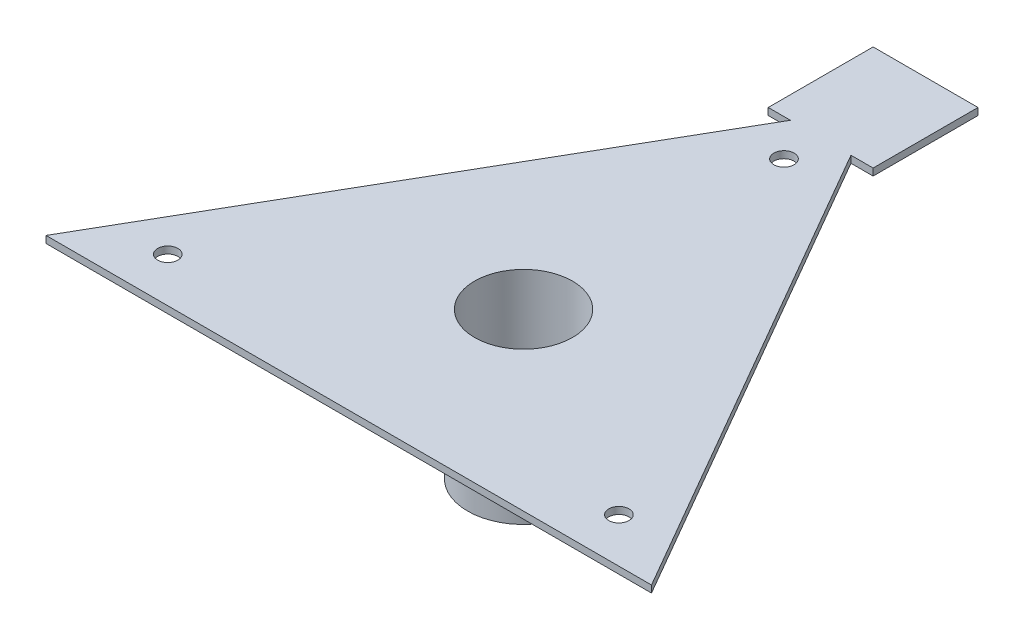
SolidWorks part; units mm, degrees
ref_plane "Front Plane" through (0, 0, 0) normal (0, 0, 1) x (1, 0, 0)
ref_plane "Top Plane" through (0, 0, 0) normal (0, 1, 0) x (1, 0, 0)
ref_plane "Right Plane" through (0, 0, 0) normal (1, 0, 0) x (0, 0, -1)
sketch "Sketch1" plane through (0, 0, 0) normal (0, 1, 0) x (1, 0, 0)
  line L0 (0, 0) -> (0, 50)
  line L1 (0, 0) -> (-43.3013, -25)
  line L2 (0, 0) -> (43.3013, -25)
  line L3 (0, 50) -> (-43.3013, -25)
  line L4 (0, 50) -> (43.3013, -25)
  line L5 (-43.3013, -25) -> (43.3013, -25)
extrude "Boss-Extrude3" add sketch "Sketch1" along normal blind 1.25 contours L4 L0 L2 | L0 L3 L1 | L1 L5 L2
sketch "Sketch5" plane through (0, 1.25, 0) normal (0, 1, 0) x (1, 0, 0)
  line L0 (0, 0) -> (0, 37.25)
  line L1 (0, 0) -> (-32.2594, -18.625)
  line L2 (0, 0) -> (32.2594, -18.625)
  circle A0 centre (0, 37.25) radius 1.45
  circle A1 centre (-32.2594, -18.625) radius 1.45
  circle A2 centre (32.2594, -18.625) radius 1.45
extrude "Cut-Extrude1" cut sketch "Sketch5" against normal blind 1.25 contours A0 | A1 | A2
sketch "Sketch6" plane through (0, 0, 0) normal (0, -1, 0) x (1, 0, 0)
  circle A0 centre (0, 0) radius 8
extrude "Boss-Extrude6" add sketch "Sketch6" along normal blind 20
sketch "Sketch8" plane through (0, -20, 0) normal (0, -1, 0) x (1, 0, 0)
  circle A0 centre (0, 0) radius 6
extrude "Cut-Extrude5" cut sketch "Sketch8" against normal blind 30
sketch "Sketch9" plane through (0, -20, 0) normal (0, -1, 0) x (1, 0, 0)
  circle A0 centre (0, 0) radius 7
extrude "Cut-Extrude7" cut sketch "Sketch9" against normal blind 25
sketch "Sketch10" plane through (0, 1.25, 0) normal (0, 1, 0) x (1, 0, 0)
  circle A0 centre (0, 0) radius 52.0839
extrude "Cut-Extrude9" cut sketch "Sketch10" against normal blind 0.25
sketch "Sketch11" plane through (0, 0, 0) normal (0, -1, 0) x (1, 0, 0)
  line L1 (-7.5, -57.5) -> (7.5, -57.5)
  line L2 (-7.5, -57.5) -> (-7.5, -42.5)
  line L3 (-7.5, -42.5) -> (7.5, -42.5)
  line L4 (7.5, -57.5) -> (7.5, -42.5)
  line L5 (-7.5, -57.5) -> (7.5, -42.5) construction
  line L6 (-7.5, -42.5) -> (7.5, -57.5) construction
  point P0 (0, -50)
extrude "Boss-Extrude9" add sketch "Sketch11" against normal blind 1
